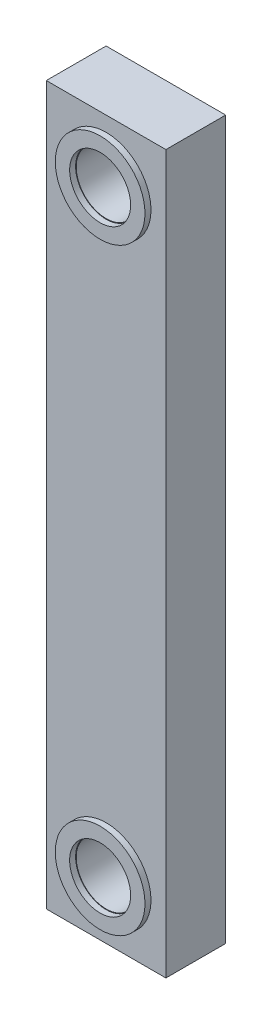
SolidWorks part; units mm, degrees
ref_plane "Ebene vorne" through (0, 0, 0) normal (0, 0, 1) x (1, 0, 0)
ref_plane "Ebene oben" through (0, 0, 0) normal (0, 1, 0) x (1, 0, 0)
ref_plane "Ebene rechts" through (0, 0, 0) normal (1, 0, 0) x (0, 0, -1)
sketch "Skizze1" plane through (0, 0, 0) normal (0, 0, 1) x (1, 0, 0)
  line L1 (0, 0) -> (20, 0)
  line L2 (0, 0) -> (0, 120)
  line L3 (0, 120) -> (20, 120)
  line L4 (20, 0) -> (20, 120)
  dimension "D1" = 20
  dimension "D2" = 120
extrude "Aufsatz-Linear austragen1" add sketch "Skizze1" along normal blind 10
sketch "Skizze2" plane through (0, 0, 10) normal (0, 0, 1) x (1, 0, 0)
  line L0 (0, 0) -> (20, 0) construction
  line L1 (20, 120) -> (0, 120) construction
  line L2 (20, 0) -> (20, 120) construction
  circle A0 centre (10, 110) radius 5.1
  circle A1 centre (10, 10) radius 5.1
  circle A2 centre (10, 110) radius 7.5
  circle A3 centre (10, 10) radius 7.5
  point P12 (0, 0)
  dimension "D1" = 10.2
  dimension "D2" = 10.2
  dimension "D7" = 15
  dimension "D3" = 10
  dimension "D4" = 10
  dimension "D5" = 10
  dimension "D6" = 10
extrude "Aufsatz-Linear austragen3" add sketch "Skizze2" along normal blind 1
sketch "Skizze5" plane through (0, 0, 10) normal (0, 0, 1) x (1, 0, 0)
  circle A0 centre (10, 110) radius 5
  circle A1 centre (10, 10) radius 5
extrude "Schnitt-Linear austragen1" cut sketch "Skizze5" against normal blind 10
